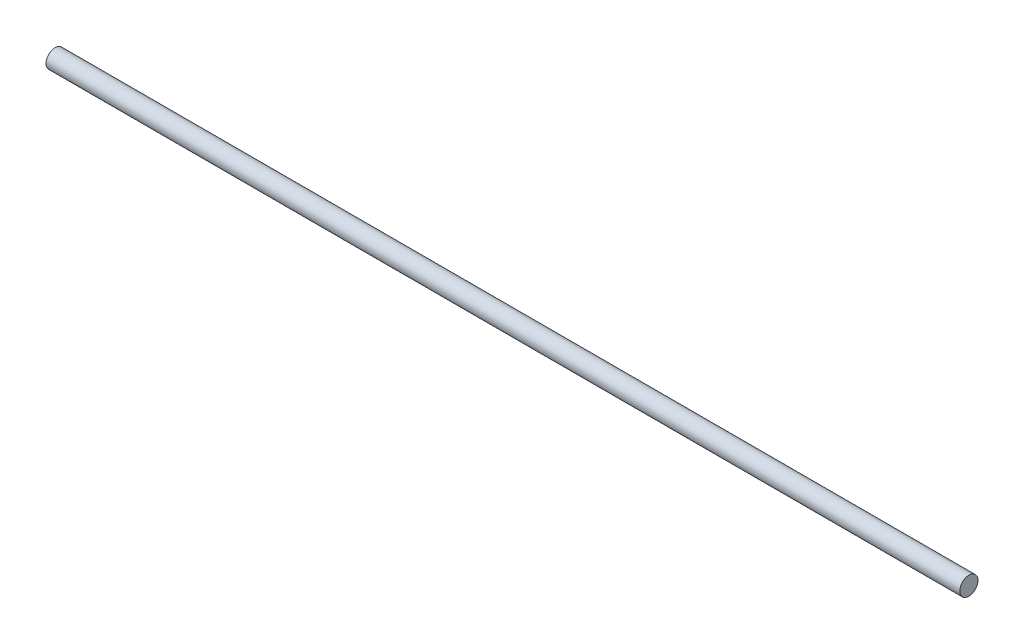
SolidWorks part; units mm, degrees
ref_plane "Front Plane" through (0, 0, 0) normal (0, 0, 1) x (1, 0, 0)
ref_plane "Top Plane" through (0, 0, 0) normal (0, 1, 0) x (1, 0, 0)
ref_plane "Right Plane" through (0, 0, 0) normal (1, 0, 0) x (0, 0, -1)
sketch "Sketch1" plane through (0, 0, 0) normal (1, 0, 0) x (0, 0, -1)
  circle A0 centre (0, 0) radius 6.35
  dimension "D1" = 12.7
extrude "Boss-Extrude1" add sketch "Sketch1" along normal blind 635
scale "Scale1" scale about centroid uniform scaling yes scale factor 1.5
